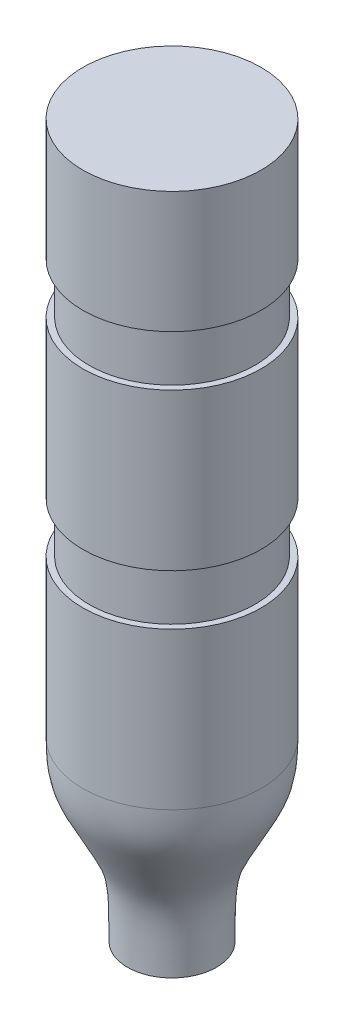
SolidWorks part; units mm, degrees
ref_plane "Front Plane" through (0, 0, 0) normal (0, 0, 1) x (1, 0, 0)
ref_plane "Top Plane" through (0, 0, 0) normal (0, 1, 0) x (1, 0, 0)
ref_plane "Right Plane" through (0, 0, 0) normal (1, 0, 0) x (0, 0, -1)
sketch "Sketch1" plane through (0, 0, 0) normal (0, 0, 1) x (1, 0, 0)
  line L0 (0, 0) -> (11.176, 0)
  line L1 (11.176, 0) -> (11.176, -15.24)
  line L2 (11.176, -15.24) -> (10.414, -15.24)
  line L3 (10.414, -15.24) -> (10.414, -21.59)
  line L4 (10.414, -21.59) -> (11.176, -21.59)
  line L5 (11.176, -21.59) -> (11.176, -41.2159)
  line L6 (11.176, -41.2159) -> (10.414, -41.2159)
  line L7 (10.414, -41.2159) -> (10.414, -47.5659)
  line L8 (10.414, -47.5659) -> (11.176, -47.5659)
  line L9 (11.176, -47.5659) -> (11.176, -67.1918)
  line L10 (5.588, -89.408) -> (5.588, -97.4675) construction
  line L11 (5.588, -89.408) -> (0, -89.408)
  line L12 (0, -89.408) -> (0, 0)
  spline S0 degree 3 poles (11.176, -67.1918) (11.176, -70.9514) (10.1829, -73.258) (5.8109, -81.1765) (5.588, -82.9459) (5.588, -89.408) knots 0 0 0 0 0.31645 0.542191 1 1 1 1
  dimension "D1" = 8.0595
  dimension "D2" = 11.176
  dimension "D3" = 5.588
  dimension "D4" = 89.408
  dimension "D5" = 7.1289
  dimension "D6" = 11.7497
  dimension "D7" = 1.6284
  dimension "D8" = 4.0489
  dimension "D9" = 22.2162
  dimension "D10" = 15.24
  dimension "D11" = 0.762
  dimension "D12" = 6.35
revolve "Revolve1" add sketch "Sketch1" angle 360 about L12
equation "\"radius\"= 0.4409in"
equation "\"length\"= 3.5236in"
